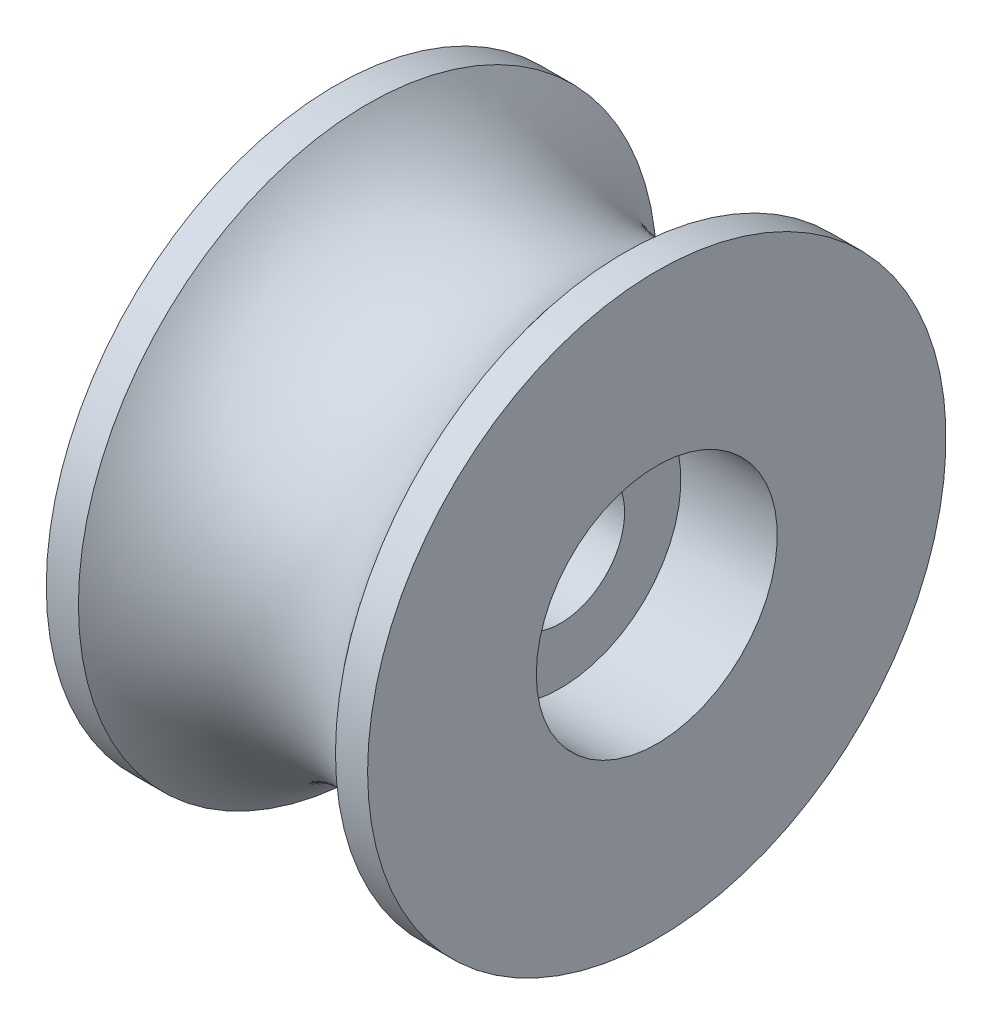
SolidWorks part; units mm, degrees
ref_plane "Front Plane" through (0, 0, 0) normal (0, 0, 1) x (1, 0, 0)
ref_plane "Top Plane" through (0, 0, 0) normal (0, 1, 0) x (1, 0, 0)
ref_plane "Right Plane" through (0, 0, 0) normal (1, 0, 0) x (0, 0, -1)
sketch "Sketch1" plane through (0, 0, 0) normal (0, 0, 1) x (1, 0, 0)
  line L0 (0, 0) -> (4.8676, 0) construction
  line L1 (0, 2) -> (2, 2)
  line L2 (2, 2) -> (2, 3.75)
  line L3 (2, 3.75) -> (5, 3.75)
  line L4 (5, 3.75) -> (5, 9)
  line L6 (0, 0) -> (0, 1.054) construction
  line L7 (0, 7) -> (3.6252, 7) construction
  line L8 (5, 9) -> (4, 9)
  line L9 (0, 2) -> (0, 7)
  arc A0 (0, 7) -> (4, 9) centre (0, 12) ccw
  dimension "D3" = 1
  dimension "D1" = 3.75
  dimension "D2" = 9
  dimension "D4" = 5
  dimension "D5" = 2
  dimension "D6" = 2
  dimension "D7" = 3
revolve "Revolve1" add sketch "Sketch1" angle 360 about L0
mirror "Mirror1" about plane through (0, 2, 0) normal (1, 0, 0) of "Revolve1"
